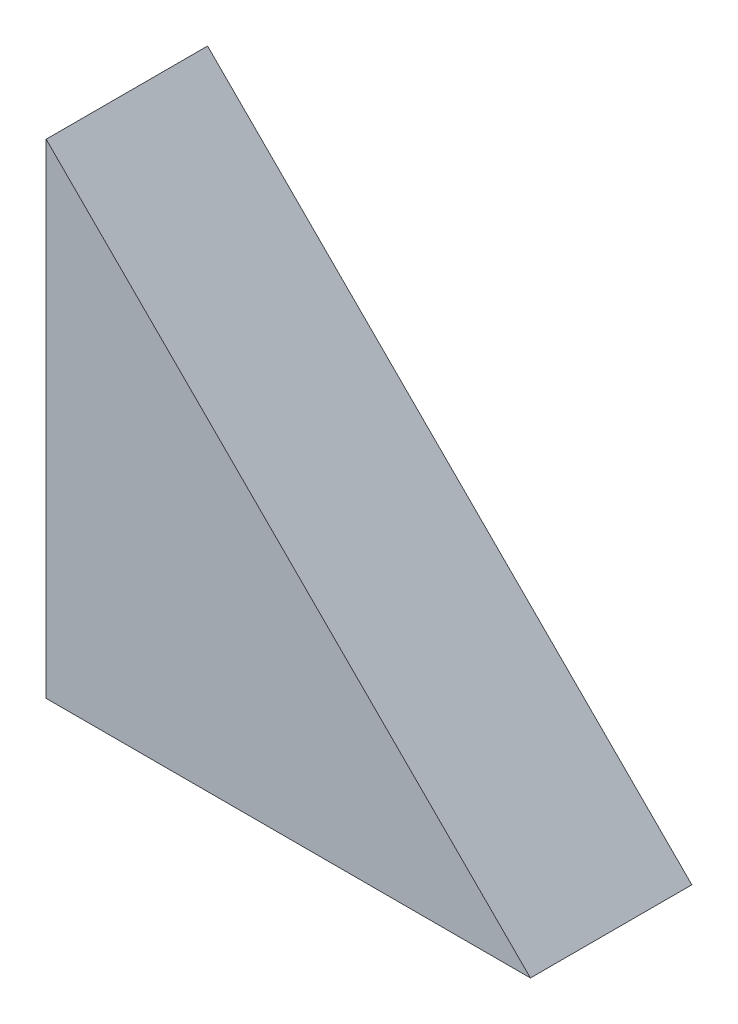
SolidWorks part; units mm, degrees
ref_plane "Alzado" through (0, 0, 0) normal (0, 0, 1) x (1, 0, 0)
ref_plane "Planta" through (0, 0, 0) normal (0, 1, 0) x (1, 0, 0)
ref_plane "Vista lateral" through (0, 0, 0) normal (1, 0, 0) x (0, 0, -1)
sketch "Croquis1" plane through (0, 0, 0) normal (0, 0, 1) x (1, 0, 0)
  line L0 (0, 38.1) -> (0, 0)
  line L1 (0, 0) -> (38.1, 0)
  line L2 (38.1, 0) -> (0, 38.1)
  point P3 (0, 36.179)
  dimension "D1" = 45
  dimension "D2" = 38.1
extrude "Saliente-Extruir1" add sketch "Croquis1" along normal mid plane 12.7
